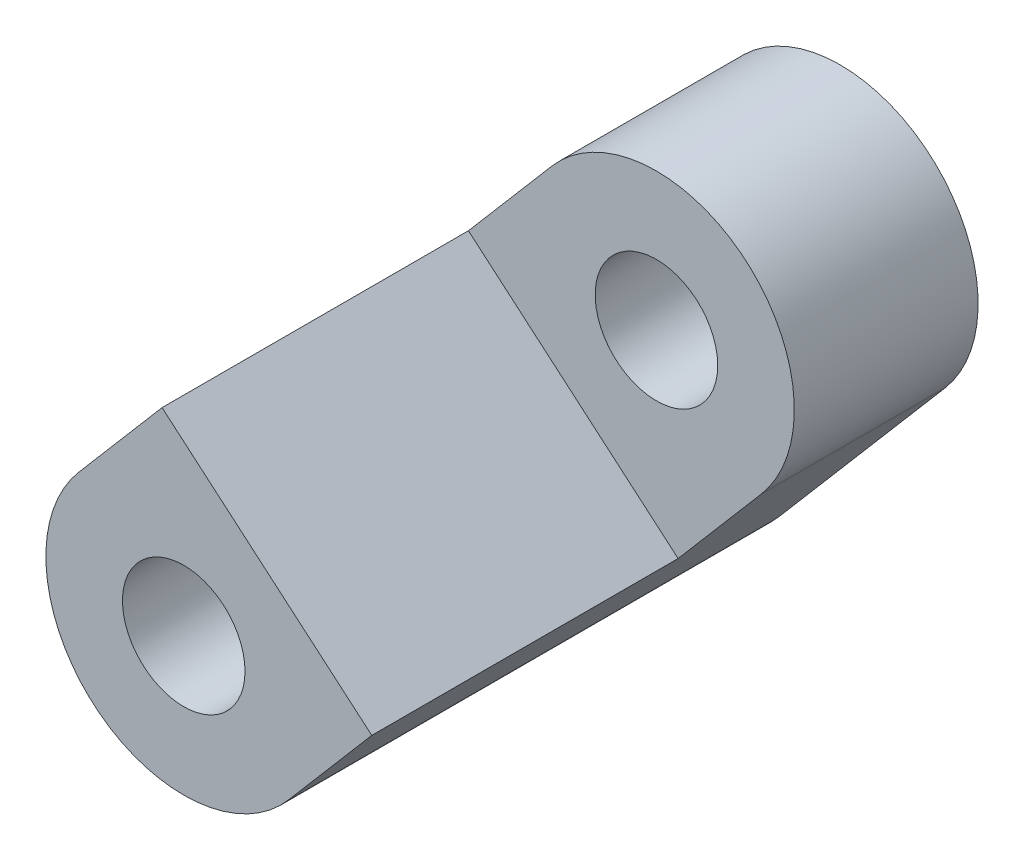
SolidWorks part; units mm, degrees
ref_plane "Front Plane" through (0, 0, 0) normal (1, 0, 0) x (0, 1, 0)
ref_plane "Top Plane" through (0, 0, 0) normal (0, 0, 1) x (0, 1, 0)
ref_plane "Right Plane" through (0, 0, 0) normal (0, 1, 0) x (-1, 0, 0)
sketch "Camera Holes" plane through (0, 0, 0) normal (0, 0, 1) x (0, 1, 0)
  line L0 (13.85, -12.85) -> (13.85, 12.85)
  line L5 (12.85, 13.85) -> (-12.85, 13.85)
  line L6 (-13.85, 12.85) -> (-13.85, -12.85)
  line L7 (-12.85, -13.85) -> (12.85, -13.85)
  line L8 (-13.85, 0) -> (13.85, 0) construction
  line L9 (0, 13.85) -> (0, -13.85) construction
  circle A0 centre (13.85, 13.85) radius 1
  circle A1 centre (13.85, -13.85) radius 1
  circle A2 centre (-13.85, 13.85) radius 1
  circle A3 centre (-13.85, -13.85) radius 1
  point P21 (0, 0)
  dimension "D2" = 25.7
  dimension "D1" = 2
sketch "Dist b/w camera bracket holes" plane through (0, 0, 0) normal (0, 0, 1) x (0, 1, 0)
  line L0 (0, 13.85) -> (0, -13.85) construction
  line L1 (-13.85, 0) -> (13.85, 0) construction
  line L2 (-13.85, 0) -> (13.85, 0) construction
  line L3 (0, 13.85) -> (0, -13.85) construction
  circle A0 centre (-10.67, 11.135) radius 1
  circle A1 centre (-10.67, -11.135) radius 1
  circle A2 centre (10.67, -11.135) radius 1
  circle A3 centre (10.67, 11.135) radius 1
  dimension "D1" = 2
  dimension "D2" = 21.34
  dimension "D3" = 22.27
sketch "Sketch3" plane through (0, 0, 0) normal (0, 0, 1) x (0, 1, 0)
  line L0 (-9.209, 12.8462) -> (-12.389, 15.5612)
  line L1 (-12.131, 9.4238) -> (-15.311, 12.1388)
  circle A0 centre (-13.85, 13.85) radius 1 construction
  circle A1 centre (-10.67, 11.135) radius 1 construction
  circle A2 centre (-13.85, 13.85) radius 1
  circle A3 centre (-10.67, 11.135) radius 1
  arc A4 (-12.131, 9.4238) -> (-9.209, 12.8462) centre (-10.67, 11.135) ccw
  arc A5 (-12.389, 15.5612) -> (-15.311, 12.1388) centre (-13.85, 13.85) ccw
  dimension "D1" = 4.5
  dimension "D2" = 4.5
extrude "Boss-Extrude1" add sketch "Sketch3" along normal blind 8
sketch "Sketch4" plane through (0, 0, 8) normal (0, 0, 1) x (1, 0, 0)
  line L0 (-12.8462, -9.209) -> (-15.5612, -12.389) construction
  line L1 (-12.1388, -15.311) -> (-9.4238, -12.131) construction
  line L2 (-12.8462, -9.209) -> (-14.2037, -10.799)
  line L3 (-10.7813, -13.721) -> (-9.4238, -12.131)
  line L4 (-10.7813, -13.721) -> (-14.2037, -10.799)
  line L5 (-14.2037, -10.799) -> (-15.5612, -12.389) construction
  arc A0 (-9.4238, -12.131) -> (-12.8462, -9.209) centre (-11.135, -10.67) ccw construction
  arc A1 (-9.4238, -12.131) -> (-12.8462, -9.209) centre (-11.135, -10.67) ccw
extrude "Cut-Extrude1" cut sketch "Sketch4" against normal blind 5
